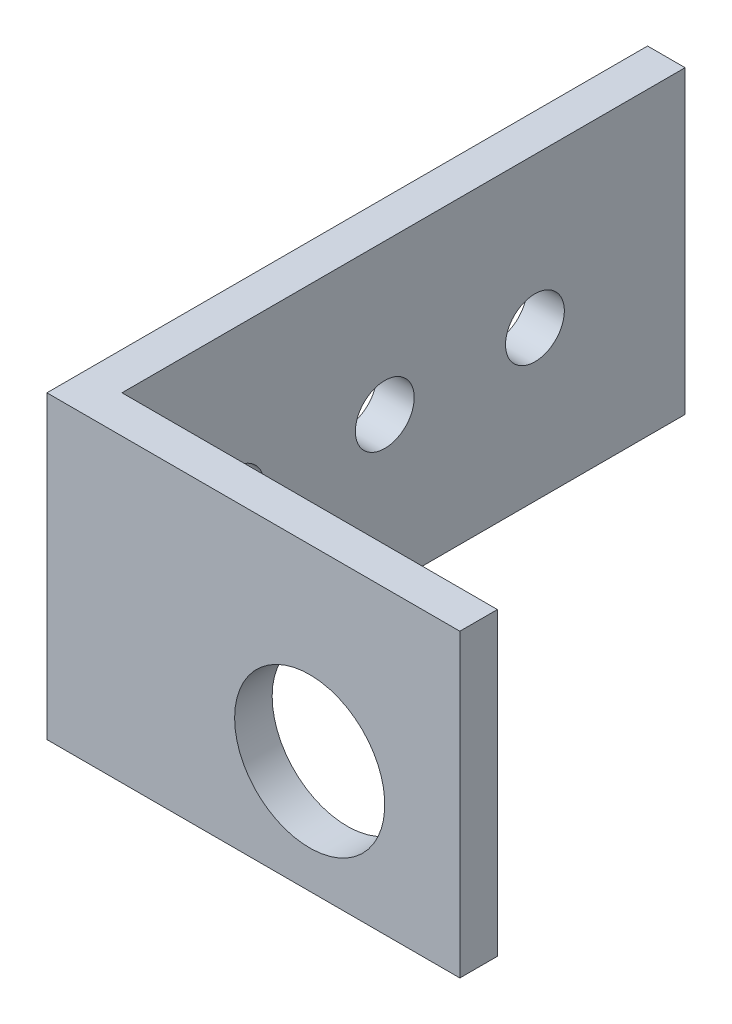
SolidWorks part; units mm, degrees
material "6061-T6 (SS)"
ref_plane "Front Plane" through (0, 0, 0) normal (0, 0, 1) x (1, 0, 0)
ref_plane "Top Plane" through (0, 0, 0) normal (0, 1, 0) x (1, 0, 0)
ref_plane "Right Plane" through (0, 0, 0) normal (1, 0, 0) x (0, 0, -1)
sketch "Sketch2" plane through (0, 0, 0) normal (0, 1, 0) x (1, 0, 0)
  line L0 (0, 0) -> (0, 50.8)
  line L1 (0, 50.8) -> (3.175, 50.8)
  line L2 (3.175, 50.8) -> (3.175, 3.175)
  line L3 (3.175, 3.175) -> (34.925, 3.175)
  line L4 (34.925, 3.175) -> (34.925, 0)
  line L5 (34.925, 0) -> (0, 0)
  dimension "D1" = 50.8
  dimension "D2" = 34.925
  dimension "D3" = 3.175
extrude "Boss-Extrude1" add sketch "Sketch2" along normal blind 25.4
sketch "Sketch3" plane through (0, 0, -3.175) normal (0, 0, -1) x (-1, 0, 0)
  line L0 (-34.925, 25.4) -> (-34.925, 0) construction
  line L1 (-34.925, 0) -> (-3.175, 0) construction
  circle A0 centre (-22.225, 9.525) radius 6.35
  dimension "D1" = 12.7
  dimension "D2" = 9.525
  dimension "D3" = 12.7
extrude "Cut-Extrude1" cut sketch "Sketch3" against normal through all
sketch "Sketch4" plane through (3.175, 0, 0) normal (1, 0, 0) x (0, 0, -1)
  line L1 (3.175, 25.4) -> (50.8, 25.4) construction
  line L2 (3.175, 0) -> (50.8, 0) construction
  line L3 (3.175, 25.4) -> (3.175, 0) construction
  circle A0 centre (25.4, 12.7) radius 2.4892
  circle A1 centre (12.7, 12.7) radius 2.4892
  circle A2 centre (38.1, 12.7) radius 2.4892
  dimension "D1" = 4.9784
  dimension "D2" = 9.525
  dimension "D3" = 12.7
  dimension "D4" = 12.7
  dimension "D5" = 12.7
  dimension "D6" = 12.7
extrude "Cut-Extrude2" cut sketch "Sketch4" against normal through all
